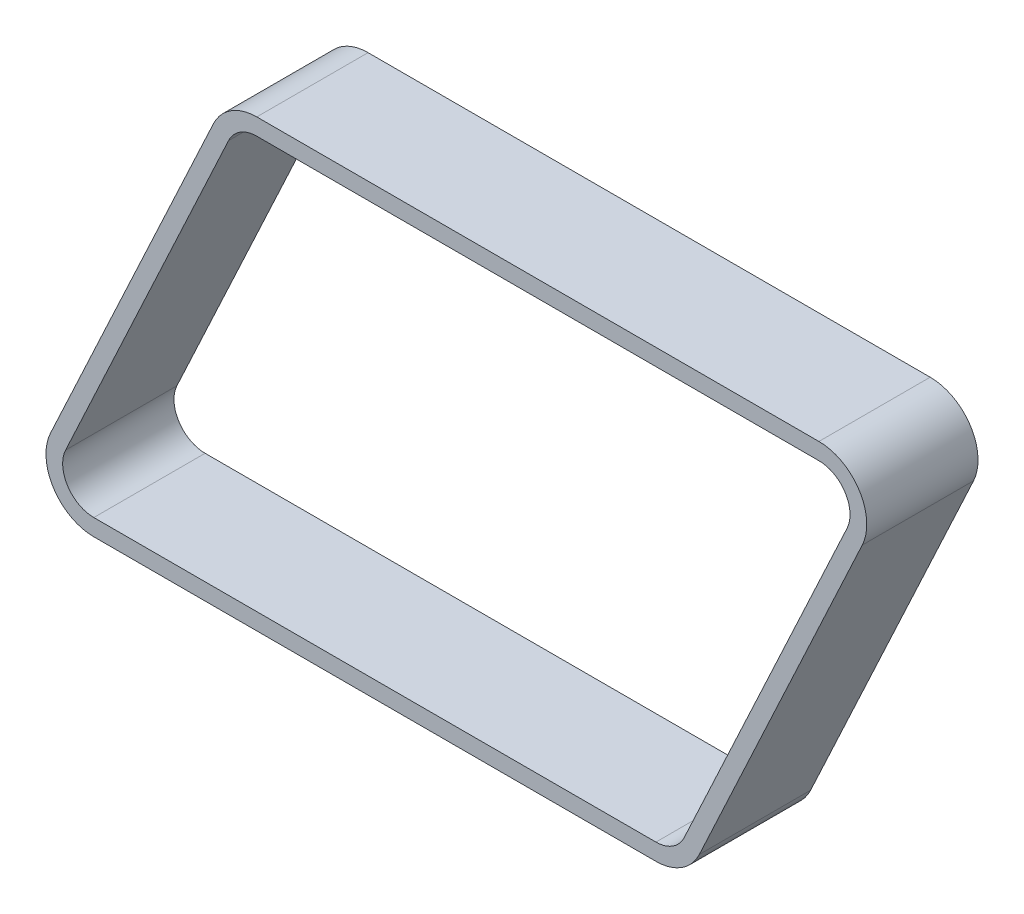
SolidWorks part; units mm, degrees
material "Natural Rubber"
ref_plane "Front Plane" through (0, 0, 0) normal (0, 0, 1) x (1, 0, 0)
ref_plane "Top Plane" through (0, 0, 0) normal (0, 1, 0) x (1, 0, 0)
ref_plane "Right Plane" through (0, 0, 0) normal (1, 0, 0) x (0, 0, -1)
sketch "Sketch1" plane through (0, 0, 0) normal (0, 0, 1) x (1, 0, 0)
  line L0 (6.7471, 0) -> (57.2598, 0)
  line L1 (2.8515, 6.115) -> (17.4942, 37.5165)
  line L2 (61.1581, 2.4835) -> (75.8008, 33.885)
  line L3 (21.3925, 40) -> (71.9052, 40)
  line L4 (0, 0) -> (6.7471, 4.2984) construction
  line L5 (0, 0) -> (3.3736, 2.1492) construction
  line L6 (78.6523, 40) -> (71.9052, 35.7016) construction
  line L7 (18.6523, 40) -> (21.3925, 35.6987) construction
  line L8 (60, 0) -> (57.2598, 4.3013) construction
  line L9 (6.7471, 1.5) -> (57.2598, 1.5)
  line L10 (59.7986, 3.1174) -> (74.4414, 34.5189)
  line L11 (21.3925, 38.5) -> (71.9052, 38.5)
  line L12 (4.2109, 5.4811) -> (18.8537, 36.8826)
  line L13 (2.5676, 3.4143) -> (2.5676, 3.4143)
  line L20 (2.5676, 3.4143) -> (5.9412, 5.5635) construction
  arc A0 (2.8515, 6.115) -> (6.7471, 0) centre (6.7471, 4.2984) ccw
  arc A1 (75.8008, 33.885) -> (71.9052, 40) centre (71.9052, 35.7016) ccw
  arc A2 (21.3925, 40) -> (17.4942, 37.5165) centre (21.3925, 35.6987) ccw
  arc A3 (57.2598, 0) -> (61.1581, 2.4835) centre (57.2598, 4.3013) ccw
  arc A4 (57.2598, 1.5) -> (59.7986, 3.1174) centre (57.2598, 4.3013) ccw
  arc A5 (74.4414, 34.5189) -> (71.9052, 38.5) centre (71.9052, 35.7016) ccw
  arc A6 (21.3925, 38.5) -> (18.8537, 36.8826) centre (21.3925, 35.6987) ccw
  arc A7 (4.2109, 5.4811) -> (6.7471, 1.5) centre (6.7471, 4.2984) ccw
  dimension "D1" = 40
  dimension "D2" = 60
  dimension "D3" = 65
  dimension "D4" = 32.5
  dimension "D5" = 8
  dimension "D6" = 32.5
  dimension "D7" = 8
  dimension "D8" = 57.5
  dimension "D9" = 5.1
  dimension "D10" = 57.5
  dimension "D11" = 5.1
  dimension "D12" = 1.5
extrude "Boss-Extrude1" add sketch "Sketch1" along normal blind 10 contours L0 A3 L2 A1 L3 A2 L1 A0 A7 L12 A6 L11 A5 L10 A4 L9
